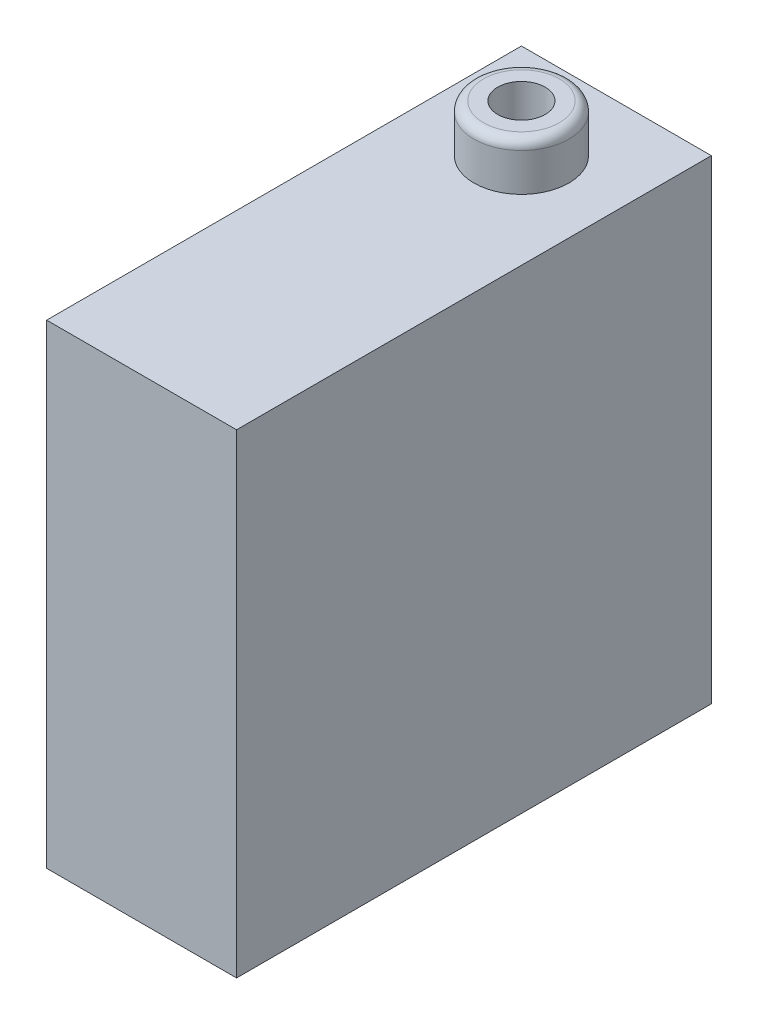
SolidWorks part; units mm, degrees
ref_plane "Front Plane" through (0, 0, 0) normal (0, 0, 1) x (1, 0, 0)
ref_plane "Top Plane" through (0, 0, 0) normal (0, 1, 0) x (1, 0, 0)
ref_plane "Right Plane" through (0, 0, 0) normal (1, 0, 0) x (0, 0, -1)
sketch "Sketch1" plane through (0, 0, 0) normal (0, 1, 0) x (1, 0, 0)
  line L1 (10, -25) -> (-10, -25)
  line L2 (10, -25) -> (10, 25)
  line L3 (10, 25) -> (-10, 25)
  line L4 (-10, -25) -> (-10, 25)
  line L5 (10, -25) -> (-10, 25) construction
  line L6 (10, 25) -> (-10, -25) construction
  point P0 (0, 0)
  dimension "D1" = 50
  dimension "D2" = 20
extrude "Boss-Extrude1" add sketch "Sketch1" along normal blind 50
sketch "Sketch2" plane through (0, 50, 0) normal (0, 1, 0) x (1, 0, 0)
  line L0 (10, 25) -> (-10, 25) construction
  circle A0 centre (0, 15) radius 5
  dimension "D1" = 10
  dimension "D2" = 10
extrude "Boss-Extrude2" add sketch "Sketch2" along normal blind 5
sketch "Sketch3" plane through (0, 55, 0) normal (0, 1, 0) x (1, 0, 0)
  circle A0 centre (0, 15) radius 2.5
  dimension "D1" = 5
extrude "Cut-Extrude1" cut sketch "Sketch3" against normal blind 5
fillet "Fillet1" radius 1 1 edges at (0, 55, -10)
